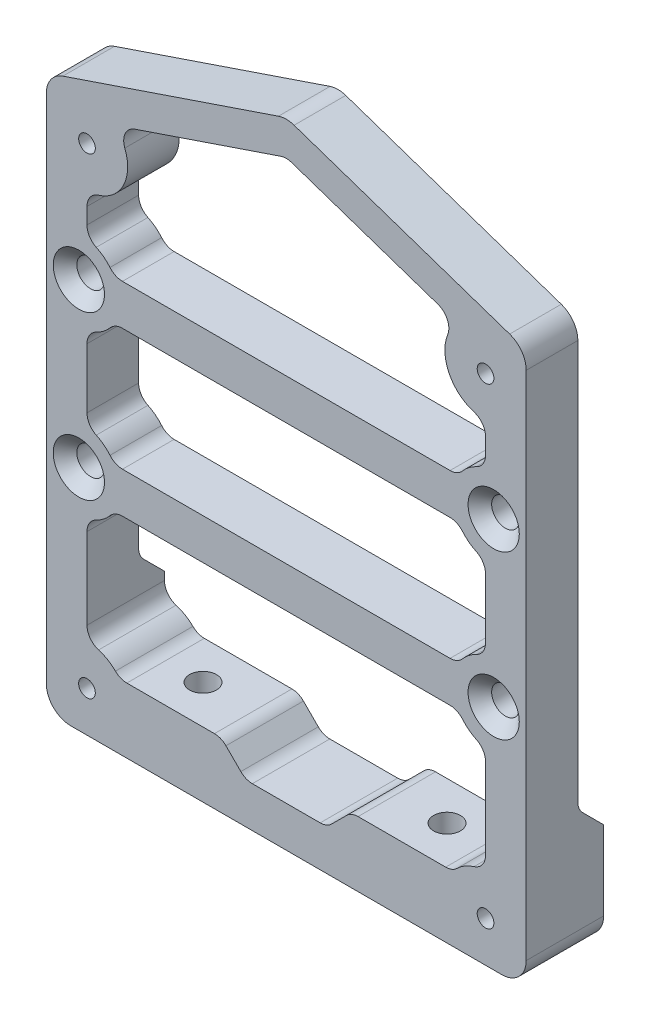
SolidWorks part; units mm, degrees
material "6061-T6 ALUMINUM"
ref_plane "Front Plane" through (0, 0, 0) normal (0, 0, 1) x (1, 0, 0)
ref_plane "Top Plane" through (0, 0, 0) normal (0, 1, 0) x (1, 0, 0)
ref_plane "Right Plane" through (0, 0, 0) normal (1, 0, 0) x (0, 0, -1)
sketch "Sketch1" plane through (0, 0, 0) normal (0, 0, 1) x (1, 0, 0)
  line L0 (-29.5, 0) -> (29.5, 0)
  line L1 (29.5, 0) -> (29.5, 68)
  line L2 (0, 0) -> (0, 100.2076) construction
  line L3 (29.5, 68) -> (0, 78)
  line L4 (-24.5, 63) -> (24.5, 63) construction
  line L5 (-24.5, 63) -> (-24.5, 5) construction
  line L6 (-24.5, 5) -> (24.5, 5) construction
  line L7 (24.5, 63) -> (24.5, 5) construction
  line L8 (0, 5) -> (0, 63) construction
  line L9 (-24.5, 34) -> (24.5, 34) construction
  line L10 (-20, 17) -> (20, 17) construction
  line L11 (-20, 17) -> (-20, 0) construction
  line L12 (-20, 0) -> (20, 0)
  line L13 (20, 17) -> (20, 0) construction
  line L14 (0, 0) -> (0, 17) construction
  line L15 (-20, 8.5) -> (20, 8.5) construction
  line L16 (-16.25, 46.5) -> (16.25, 46.5) construction
  line L17 (-16.25, 46.5) -> (-16.25, 32) construction
  line L18 (-16.25, 32) -> (16.25, 32) construction
  line L19 (16.25, 46.5) -> (16.25, 32) construction
  line L20 (0, 32) -> (0, 46.5) construction
  line L21 (-16.25, 39.25) -> (16.25, 39.25) construction
  line L22 (-29.5, 0) -> (-29.5, 68)
  line L23 (-29.5, 68) -> (0, 78)
  point P4 (0, 0)
  point P8 (0, 34)
  point P12 (0, 39.25)
  point P15 (0, 8.5)
  dimension "D1" = 49
  dimension "D2" = 58
  dimension "D3" = 5
  dimension "D4" = 5
  dimension "D5" = 17
  dimension "D6" = 40
  dimension "D7" = 14.5
  dimension "D8" = 32.5
  dimension "D9" = 15
  dimension "D10" = 5
  dimension "D11" = 15
extrude "Boss-Extrude1" add sketch "Sketch1" along normal mid plane 9.525 contours L23 L22 L0 L1 L3
sketch "Sketch2" plane through (29.5, 0, 0) normal (1, 0, 0) x (0, 0, -1)
  line L0 (1.5875, 78) -> (1.5875, 15.875)
  line L1 (-4.7625, 78) -> (4.7625, 78) construction
  line L2 (1.5875, 15.875) -> (4.7625, 12.7)
  line L3 (4.7625, 0) -> (4.7625, 68) construction
  line L4 (1.5875, 78) -> (4.7625, 78)
  line L5 (4.7625, 78) -> (4.7625, 12.7)
  dimension "D1" = 12.7
  dimension "D2" = 3.175
  dimension "D3" = 135
extrude "Cut-Extrude1" cut sketch "Sketch2" against normal through all
fillet "Fillet1" radius 3 5 edges at (29.5, 68, 1.5875) (0, 78, 1.5875) (-29.5, 68, 1.5875) (-29.5, 0, 0) (29.5, 0, 0)
hole_wizard "M2.5x0.45 Tapped Hole1" positions "Sketch3" profile "Sketch4" tap size "M2.5x0.45" standard "ANSI Metric" end condition through all
sketch "Sketch3" plane through (0, 0, 4.7625) normal (0, 0, 1) x (1, 0, 0)
  line L0 (-24.5, 63) -> (-24.5, 5) construction
  line L1 (24.5, 63) -> (24.5, 5) construction
  point P3 (-24.5, 5)
  point P6 (24.5, 5)
  point P9 (-24.5, 63)
  point P13 (24.5, 63)
  dimension "D1" = 58
sketch "Sketch4" plane through (-24.5, 5, 4.7625) normal (1, 0, 0) x (0, -1, 0)
  line L0 (0, 0) -> (0, 9.525)
  line L1 (0, 9.525) -> (1.025, 9.525)
  line L2 (1.025, 9.525) -> (1.025, 0)
  line L5 (1.025, 0) -> (0, 0)
  line L11 (0, -6.35) -> (0, 107.95) construction
  dimension "Thru Tap Drill Dia." = 2.05
  dimension "Thru Tap Drill Depth" = 9.525
hole_wizard "M4x0.7 Tapped Hole1" positions "Sketch5" profile "Sketch6" tap size "M4x0.7" standard "ANSI Metric"
sketch "Sketch5" plane through (0, 0, 0) normal (0, -1, 0) x (-1, 0, 0)
  point P0 (-15, 0)
  point P2 (15, 0)
  dimension "D1" = 15
  dimension "D2" = 15
sketch "Sketch6" plane through (15, 0, 0) normal (1, 0, 0) x (0, 0, -1)
  line L0 (0, 0) -> (0, 12.4914)
  line L1 (0, 12.4914) -> (1.65, 11.5)
  line L2 (1.65, 11.5) -> (1.65, 0)
  line L5 (1.65, 0) -> (0, 0)
  line L10 (0, 12.4914) -> (-1.65, 11.5) construction
  line L11 (0, -6.35) -> (0, 107.95) construction
  dimension "Tap Drill Dia." = 3.3
  dimension "Tap Drill Depth" = 11.5
  dimension "Drill Angle" = 118
hole_wizard "CSK for M3 Flat Head Machine Screw1" positions "Sketch10" profile "Sketch11" countersink size "M3" standard "ANSI Metric" end condition through all
sketch "Sketch10" plane through (0, 0, 4.7625) normal (0, 0, 1) x (1, 0, 0)
  line L0 (-16.25, 32) -> (16.25, 32) construction
  line L1 (-16.25, 32) -> (16.25, 32) construction
  line L2 (0, 32) -> (0, 46.9074) construction
  line L3 (-29.5, 3) -> (-29.5, 65.8493) construction
  point P0 (-25.5, 28)
  point P10 (25.5, 28)
  point P14 (-25.5, 48)
  point P19 (25.5, 48)
  dimension "D1" = 4
  dimension "D2" = 4
  dimension "D3" = 20
sketch "Sketch11" plane through (-25.5, 28, 4.7625) normal (1, 0, 0) x (0, -1, 0)
  line L0 (0, 0) -> (0, 9.525)
  line L1 (0, 9.525) -> (1.7, 9.525)
  line L2 (1.7, 9.525) -> (1.7, 1.45)
  line L3 (1.7, 1.45) -> (3.15, 0)
  line L5 (3.15, 0) -> (0, 0)
  line L6 (-1.7, 1.45) -> (-3.15, 0) construction
  line L11 (0, -6.35) -> (0, 107.95) construction
  dimension "Thru Hole Dia." = 3.4
  dimension "Thru Hole Depth" = 9.525
  dimension "Near C'Sink Dia." = 6.3
  dimension "Near C'Sink Angle" = 90
sketch "Sketch7" plane through (0, 0, 4.7625) normal (0, 0, 1) x (1, 0, 0)
  line L0 (-16.25, 32) -> (16.25, 32) construction
  line L1 (-16.25, 32) -> (16.25, 32) construction
  line L3 (0, 0) -> (0, 77.8323) construction
  line L4 (-24.5, 32.899) -> (-24.5, 58)
  line L6 (-29.5, 3) -> (-29.5, 65.8493) construction
  line L7 (24.5, 58) -> (24.5, 32.899)
  line L8 (-24.5, 23.101) -> (-24.5, 10)
  line L11 (-26.5, 0) -> (26.5, 0) construction
  line L12 (24.5, 23.101) -> (24.5, 10)
  line L13 (-21.0669, 66.6351) -> (0, 73.7764)
  line L15 (-27.4631, 68.6905) -> (-0.9631, 77.6735) construction
  line L16 (21.0669, 66.6351) -> (0, 73.7764)
  line L17 (5, 5) -> (-5, 5)
  line L18 (-20.5, 8) -> (-8, 8)
  line L19 (-8, 8) -> (-5, 5)
  line L20 (-25.5, 48) -> (25.5, 48) construction
  line L21 (8, 8) -> (5, 5)
  line L22 (20.5, 8) -> (8, 8)
  line L23 (21.1699, 30.5) -> (-21.1699, 30.5)
  line L24 (21.1699, 25.5) -> (-21.1699, 25.5)
  line L25 (-25.5, 28) -> (25.5, 28) construction
  line L26 (-21.1699, 45.5) -> (21.1699, 45.5)
  line L27 (0, 0) -> (0, 100.2076) construction
  line L28 (-21.1699, 50.5) -> (21.1699, 50.5)
  arc A0 (0.9631, 77.6735) -> (-0.9631, 77.6735) centre (0, 74.8323) ccw construction
  arc A1 (-24.5, 10) -> (-20.5, 8) centre (-24.5, 5) cw
  arc A2 (24.5, 10) -> (20.5, 8) centre (24.5, 5) ccw
  arc A3 (-21.0669, 66.6351) -> (-24.5, 58) centre (-24.5, 63) cw
  arc A4 (21.0669, 66.6351) -> (24.5, 58) centre (24.5, 63) ccw
  circle A5 centre (-25.5, 28) radius 5
  circle A6 centre (25.5, 28) radius 5
  circle A7 centre (-25.5, 48) radius 5
  circle A8 centre (25.5, 48) radius 5
  point P5 (0, 30.5)
  point P13 (-33.3136, 64.601)
  point P16 (0, 45.5)
  point P25 (0, 5)
  point P27 (0, 25.5)
  point P38 (0, 5)
  point P41 (0, 58)
  point P53 (0, 30.5)
  point P54 (0, 25.5)
  point P64 (0, 45.5)
  point P68 (24.8369, 58)
  point P71 (0, 0)
  point P72 (-24.5, 57.5315)
  dimension "D4" = 5
  dimension "D5" = 10
  dimension "D14" = 10
  dimension "D2" = 2.5
  dimension "D3" = 5
  dimension "D6" = 8
  dimension "D8" = 4
  dimension "D9" = 5
  dimension "D10" = 10
  dimension "D11" = 135
  dimension "D12" = 5
  dimension "D13" = 2.5
extrude "Cut-Extrude2" cut sketch "Sketch7" against normal through all
fillet "Fillet2" radius 2 31 edges at (24.5, 10, 0) (-24.5, 10, 0) (21.0669, 66.6351, 1.5875) (0, 73.7764, 1.5875) (-21.0669, 66.6351, 1.5875) (8, 8, 0) (5, 5, 0) (-8, 8, 0) (-5, 5, 0) (-20.5, 8, 0) (27, 15.875, -1.5875) (-27, 15.875, -1.5875) (20.5, 8, 0) (21.1699, 30.5, 1.5875) (24.5, 32.899, 1.5875) (24.5, 23.101, 1.5875) (21.1699, 25.5, 1.5875) (-21.1699, 25.5, 1.5875) (-24.5, 23.101, 1.5875) (-21.1699, 30.5, 1.5875) (-24.5, 32.899, 1.5875) (24.5, 52.899, 1.5875) (24.5, 43.101, 1.5875) (21.1699, 45.5, 1.5875) (-21.1699, 45.5, 1.5875) (-24.5, 52.899, 1.5875) (-24.5, 43.101, 1.5875) (24.5, 58, 1.5875) (21.1699, 50.5, 1.5875) (-21.1699, 50.5, 1.5875) (-24.5, 58, 1.5875)
